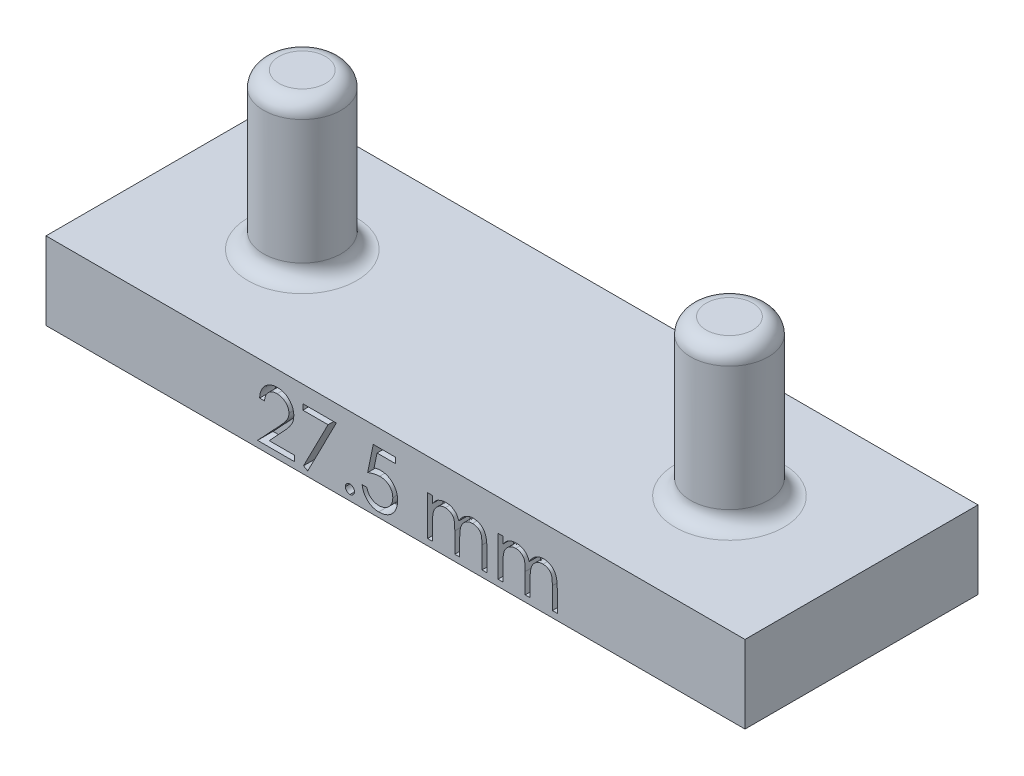
SolidWorks part; units mm, degrees
ref_plane "Front Plane" through (0, 0, 0) normal (0, 0, 1) x (1, 0, 0)
ref_plane "Top Plane" through (0, 0, 0) normal (0, 1, 0) x (1, 0, 0)
ref_plane "Right Plane" through (0, 0, 0) normal (1, 0, 0) x (0, 0, -1)
sketch "Sketch1" plane through (0, 0, 0) normal (0, 1, 0) x (1, 0, 0)
  circle A0 centre (-41.8213, 3.1021) radius 2.5
  circle A1 centre (-14.3213, 3.1021) radius 2.5
  dimension "D1" = 27.5
extrude "Boss-Extrude1" add sketch "Sketch1" along normal blind 10
sketch "Sketch2" plane through (0, 0, 0) normal (0, -1, 0) x (1, 0, 0)
  line L1 (-50.8213, 4.3979) -> (-5.8213, 4.3979)
  line L2 (-50.8213, 4.3979) -> (-50.8213, -10.6021)
  line L3 (-50.8213, -10.6021) -> (-5.8213, -10.6021)
  line L4 (-5.8213, 4.3979) -> (-5.8213, -10.6021)
  circle A0 centre (-41.8213, -3.1021) radius 2.5 construction
  dimension "D1" = 45
  dimension "D2" = 15
  dimension "D3" = 7.5
  dimension "D4" = 9
extrude "Boss-Extrude2" add sketch "Sketch2" along normal blind 5
sketch "Sketch3" plane through (0, 0, 4.3979) normal (0, 0, 1) x (1, 0, 0)
  line L0 (-7.1347, -4.5918) -> (-47.7505, -4.5918) construction
  text T0 "27.5 mm"
extrude "Cut-Extrude1" cut sketch "Sketch3" against normal blind 1
fillet "Fillet1" radius 1 4 edges at (-41.8213, 0, -0.6021) (-14.3213, 0, -5.6021) (-14.3213, 10, -0.6021) (-41.8213, 10, -0.6021)
